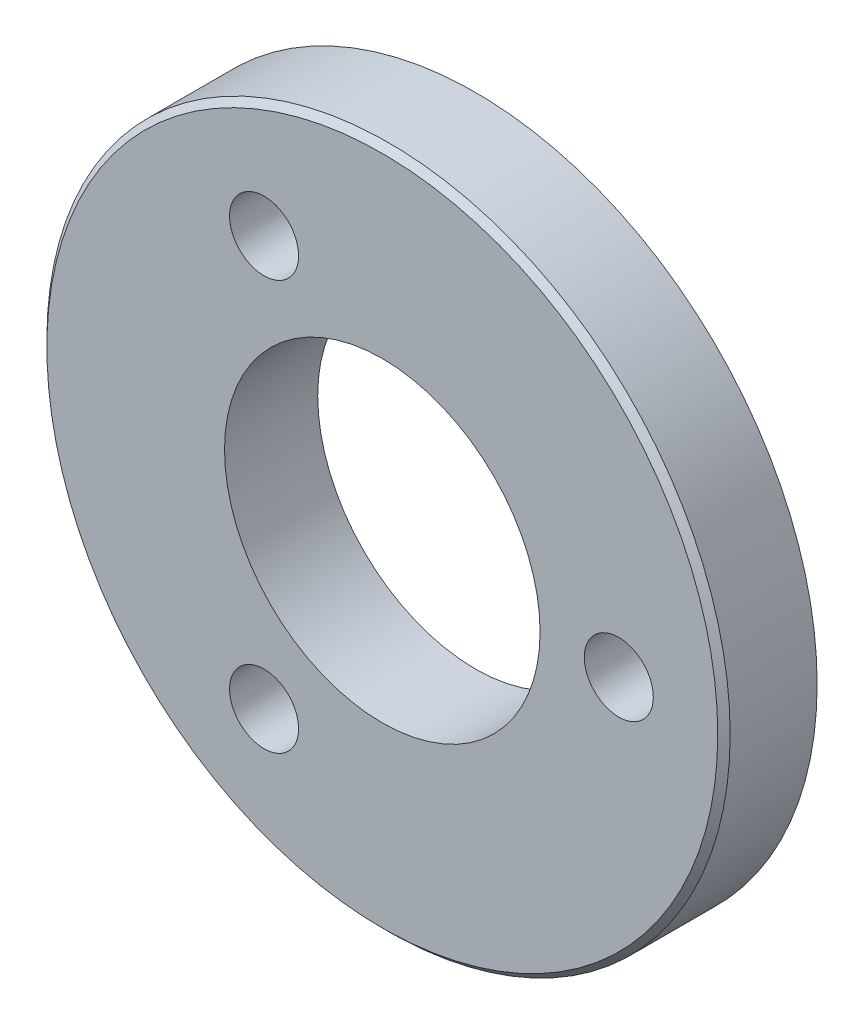
SolidWorks part; units mm, degrees
ref_plane "Front Plane" through (0, 0, 0) normal (0, 0, 1) x (1, 0, 0)
ref_plane "Top Plane" through (0, 0, 0) normal (0, 1, 0) x (1, 0, 0)
ref_plane "Right Plane" through (0, 0, 0) normal (1, 0, 0) x (0, 0, -1)
sketch "Sketch1" plane through (0, 0, 0) normal (0, 0, 1) x (1, 0, 0)
  line L0 (0, 0) -> (0, 11.9147) construction
  line L1 (-0.0301, 5.8144) -> (-0.0301, 17.7291) construction
  line L2 (-31.4215, 0) -> (34.6021, 0) construction
  circle A0 centre (0, 0) radius 27.5
  circle A1 centre (-9.5171, 16.484) radius 2.7781
  circle A2 centre (19.0341, 0) radius 2.7781
  circle A3 centre (-9.5171, -16.484) radius 2.7781
  circle A4 centre (0, 0) radius 19.0341 construction
  circle A5 centre (0, 0) radius 12.7
  point P18 (0, 0)
  dimension "D1" = 5.5562
  dimension "D2" = 55
  dimension "D5" = 6.3341
  dimension "D3" = 25.4
  dimension "D4" = 3
extrude "Boss-Extrude1" add sketch "Sketch1" along normal blind 7.5
chamfer "Chamfer1" distance 0.5 angle 45 1 edges at (27.5, 0, 7.5)
